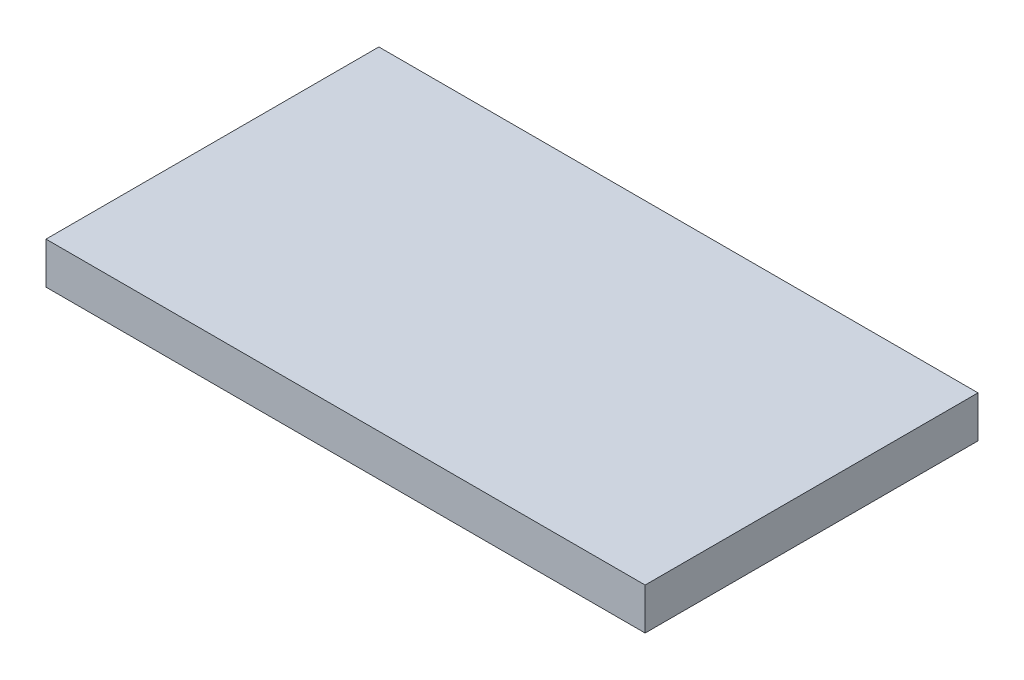
SolidWorks part; units mm, degrees
material "1.0553 (S355J0)"
ref_plane "Front Plane" through (0, 0, 0) normal (0, 0, 1) x (1, 0, 0)
ref_plane "Top Plane" through (0, 0, 0) normal (0, 1, 0) x (1, 0, 0)
ref_plane "Right Plane" through (0, 0, 0) normal (1, 0, 0) x (0, 0, -1)
sketch "Sketch1" plane through (0, 0, 0) normal (0, 1, 0) x (1, 0, 0)
  line L1 (-180, 0) -> (180, 0)
  line L2 (-180, 0) -> (-180, 200)
  line L3 (-180, 200) -> (180, 200)
  line L4 (180, 0) -> (180, 200)
  dimension "D1" = 360
  dimension "D2" = 200
extrude "Boss-Extrude1" add sketch "Sketch1" against normal blind 25
